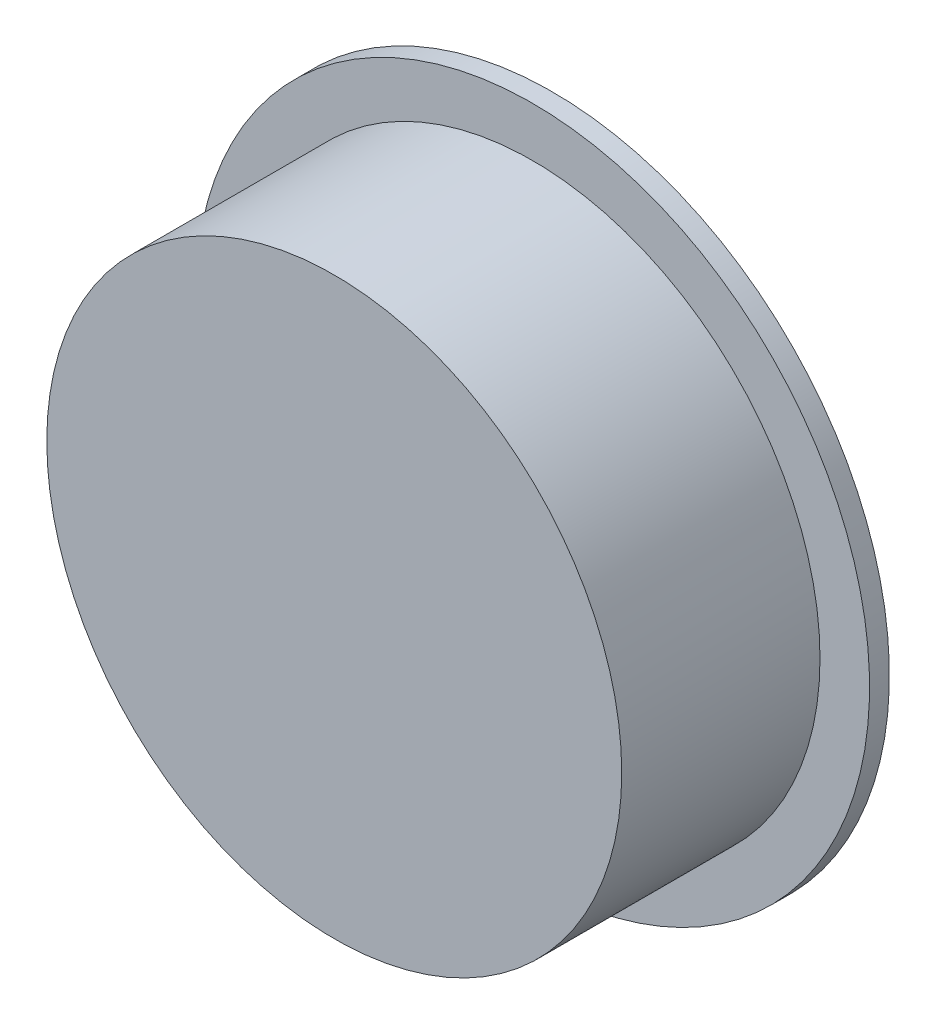
SolidWorks part; units mm, degrees
ref_plane "Front Plane" through (0, 0, 0) normal (0, 0, 1) x (1, 0, 0)
ref_plane "Top Plane" through (0, 0, 0) normal (0, 1, 0) x (1, 0, 0)
ref_plane "Right Plane" through (0, 0, 0) normal (1, 0, 0) x (0, 0, -1)
sketch "Sketch1" plane through (0, 0, 0) normal (0, 0, 1) x (1, 0, 0)
  circle A0 centre (0, 0) radius 7.25
  dimension "D1" = 14.5
extrude "Boss-Extrude1" add sketch "Sketch1" along normal blind 5
sketch "Sketch3" plane through (0, 0, 0) normal (0, 0, -1) x (-1, 0, 0)
  circle A0 centre (0, 0) radius 8.5
  dimension "D1" = 17
extrude "Boss-Extrude2" add sketch "Sketch3" along normal blind 0.5
sketch "Sketch5" plane through (0, 0, -0.5) normal (0, 0, -1) x (-1, 0, 0)
  circle A0 centre (0, 0) radius 1.75
  dimension "D1" = 3.5
extrude "Cut-Extrude1" cut sketch "Sketch5" against normal blind 0.75
